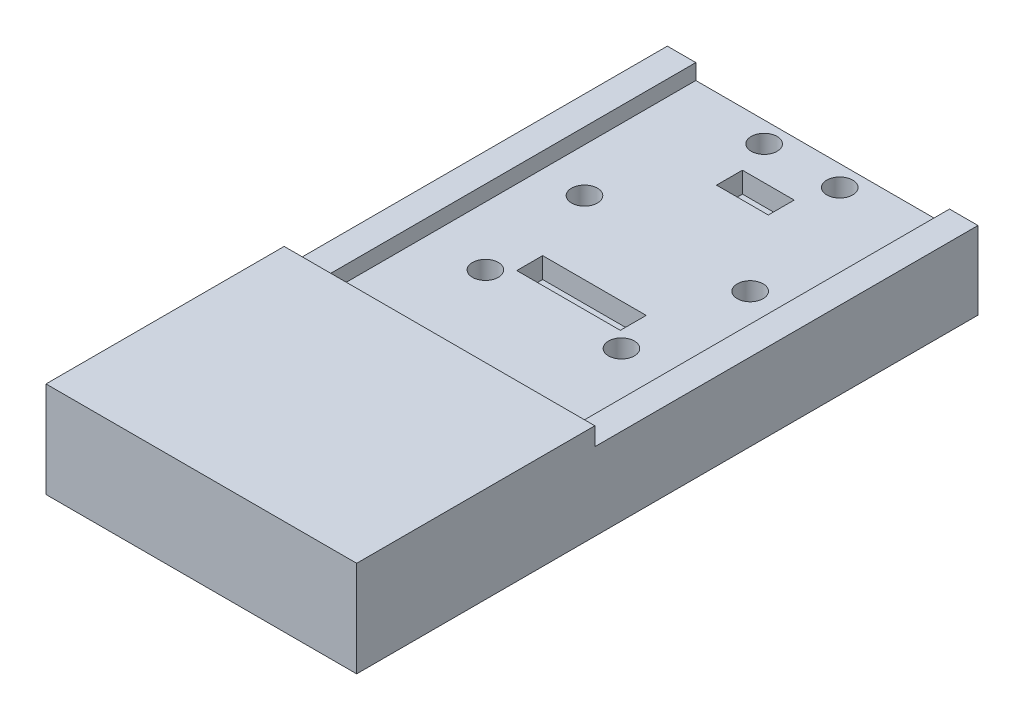
SolidWorks part; units mm, degrees
ref_plane "Front Plane" through (0, 0, 0) normal (0, 0, 1) x (1, 0, 0)
ref_plane "Top Plane" through (0, 0, 0) normal (0, 1, 0) x (1, 0, 0)
ref_plane "Right Plane" through (0, 0, 0) normal (1, 0, 0) x (0, 0, -1)
sketch "Sketch1" plane through (0, 0, 0) normal (0, 1, 0) x (1, 0, 0)
  line L0 (0, 30) -> (0, -30) construction
  line L1 (-15, 30) -> (15, 30)
  line L2 (-15, 30) -> (-15, -30)
  line L3 (-15, -30) -> (15, -30)
  line L4 (15, 30) -> (15, -30)
  circle A0 centre (-8, 15) radius 1.25
  circle A1 centre (8, 15) radius 1.25
  dimension "5" = 2.5
  dimension "D1" = 60
  dimension "D2" = 30
  dimension "D3" = 30
  dimension "D4" = 8
  dimension "D5" = 15
extrude "Boss-Extrude1" add sketch "Sketch1" against normal blind 6
ref_plane "Plane1" through (0, -6, 0) normal (0, -1, 0) x (-1, 0, 0)
sketch "Sketch2" plane through (0, -6, 0) normal (0, -1, 0) x (-1, 0, 0)
  circle A0 centre (-8, 15) radius 2.25
  circle A1 centre (8, 15) radius 2.25
  dimension "D1" = 4.5
extrude "Cut-Extrude1" cut sketch "Sketch2" against normal blind 2
sketch "Sketch3" plane through (0, 0, 0) normal (0, 1, 0) x (1, 0, 0)
  line L0 (0, 36.5143) -> (0, -37.671) construction
  line L1 (-15, -30) -> (15, -30) construction
  line L2 (-15, 30) -> (-12.25, 30)
  line L3 (-15, 30) -> (-15, -30)
  line L4 (-15, -30) -> (-12.25, -30)
  line L5 (-12.25, 30) -> (-12.25, -30)
  line L7 (15, 30) -> (12.25, 30)
  line L8 (15, 30) -> (15, -30)
  line L9 (15, -30) -> (12.25, -30)
  line L10 (12.25, 30) -> (12.25, -30)
  dimension "D1" = 12.25
extrude "Boss-Extrude2" add sketch "Sketch3" along normal blind 1.5
sketch "Sketch4" plane through (0, 0, 0) normal (0, 1, 0) x (1, 0, 0)
  line L0 (0, 37.8943) -> (0, -36.8227) construction
  line L2 (-2.5, 24.75) -> (2.5, 24.75)
  line L3 (-2.5, 24.75) -> (-2.5, 22.25)
  line L4 (-2.5, 22.25) -> (2.5, 22.25)
  line L5 (2.5, 24.75) -> (2.5, 22.25)
  line L6 (-5, 7.96) -> (5, 7.96)
  line L7 (-5, 7.96) -> (-5, 5.46)
  line L8 (-5, 5.46) -> (5, 5.46)
  line L9 (5, 7.96) -> (5, 5.46)
  circle A0 centre (-3.65, 28) radius 1.25
  circle A1 centre (3.65, 28) radius 1.25
  circle A2 centre (-6.57, 4) radius 1.25
  circle A3 centre (6.57, 4) radius 1.25
  point P11 (-2.5, 23.5)
  point P20 (-5, 6.71)
  dimension "D2" = 2.5
  dimension "D9" = 10
  dimension "D1" = 28
  dimension "D3" = 2.5
  dimension "D4" = 5
  dimension "D5" = 4.5
  dimension "D6" = 7.3
  dimension "D7" = 4
  dimension "D8" = 13.14
  dimension "D10" = 2.5
  dimension "D11" = 2.71
extrude "Cut-Extrude2" cut sketch "Sketch4" against normal blind 2
sketch "Sketch5" plane through (0, 0, 0) normal (0, 1, 0) x (1, 0, 0)
  line L0 (-15, 30) -> (-15, -30) construction
  line L1 (-15, -7) -> (15, -7)
  line L2 (-15, -7) -> (-15, -30)
  line L3 (-15, -30) -> (15, -30)
  line L4 (15, -7) -> (15, -30)
  dimension "D1" = 7
extrude "Boss-Extrude3" add sketch "Sketch5" along normal blind 3.25
